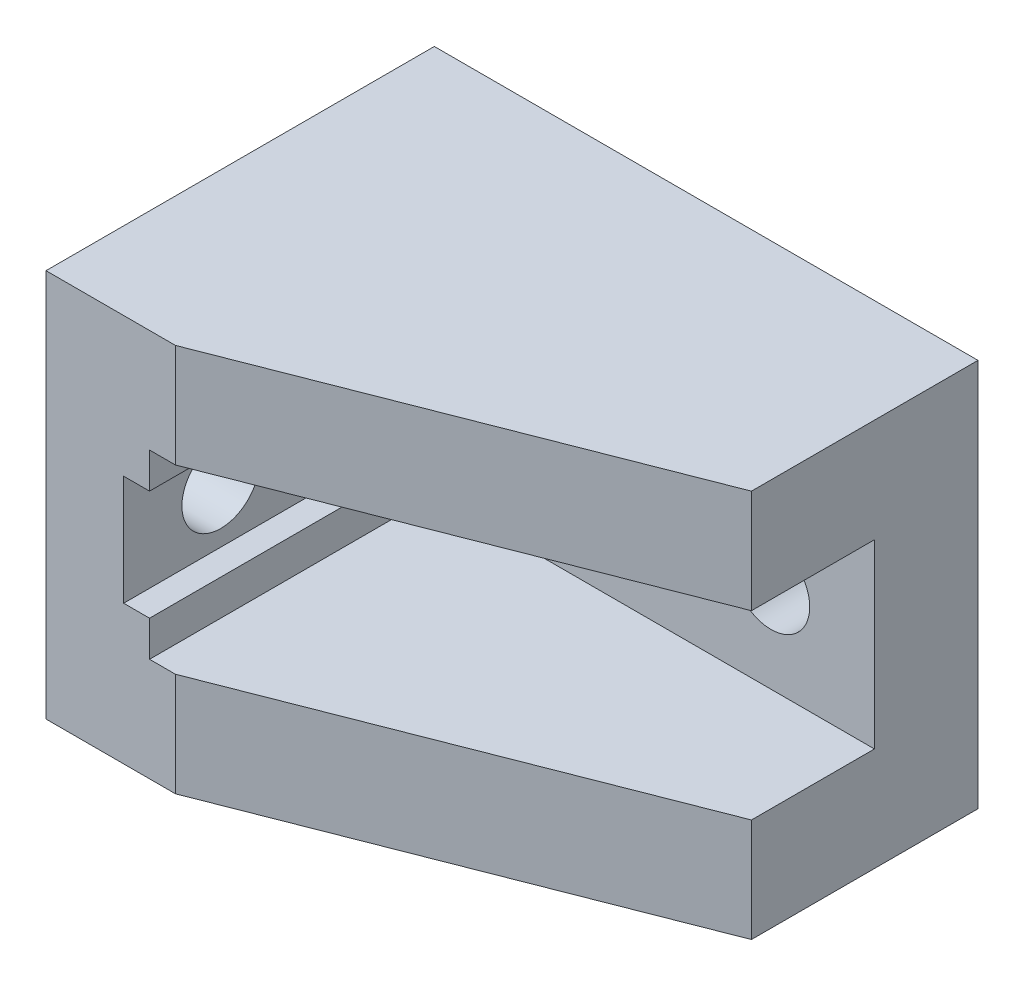
SolidWorks part; units mm, degrees
ref_plane "Front Plane" through (0, 0, 0) normal (0, 0, 1) x (1, 0, 0)
ref_plane "Top Plane" through (0, 0, 0) normal (0, 1, 0) x (1, 0, 0)
ref_plane "Right Plane" through (0, 0, 0) normal (1, 0, 0) x (0, 0, -1)
sketch "Sketch2" plane through (0, 0, 0) normal (0, 1, 0) x (1, 0, 0)
  line L0 (10, -30) -> (42, -17.5)
  line L1 (0, 0) -> (42, 0)
  line L2 (0, 0) -> (0, -30)
  line L3 (0, -30) -> (10, -30)
  line L4 (42, 0) -> (42, -17.5)
  dimension "D1" = 17.5
  dimension "D2" = 10
  dimension "D3" = 42
  dimension "D4" = 30
extrude "Boss-Extrude1" add sketch "Sketch2" along normal blind 30
shell "Shell1" thickness 8
sketch "Sketch3" plane through (8, 0, 0) normal (1, 0, 0) x (0, 0, -1)
  line L0 (-30, 15) -> (0, 15) construction
  line L1 (-30, 22) -> (-30, 8) construction
  line L3 (-15, 22) -> (-15, 8) construction
  line L7 (0, 30) -> (0, 0) construction
  line L8 (-17.5, 22) -> (-8, 22) construction
  circle A0 centre (-22.5, 15) radius 3
  circle A1 centre (-7.5, 15) radius 3
  point P8 (-15, 15)
  dimension "D2" = 6
  dimension "D1" = 15
extrude "Cut-Extrude1" cut sketch "Sketch3" against normal blind 30
sketch "Sketch4" plane through (0, 0, 8) normal (0, 0, 1) x (1, 0, 0)
  line L0 (8, 15) -> (42, 15) construction
  line L2 (42, 22) -> (42, 8) construction
  line L3 (25, 15) -> (25, 8) construction
  line L4 (42, 8) -> (8, 8) construction
  circle A0 centre (16, 15) radius 3
  circle A1 centre (34, 15) radius 3
  dimension "D1" = 18
  dimension "D2" = 6
extrude "Cut-Extrude2" cut sketch "Sketch4" against normal blind 10
sketch "Sketch6" plane through (0, 0, 0) normal (-1, 0, 0) x (0, 0, 1)
  line L4 (0, 0) -> (30, 0)
  line L5 (30, 0) -> (30, 30)
  line L6 (30, 30) -> (0, 30)
  line L7 (0, 30) -> (0, 0)
  line L8 (0, 0) -> (30, 0)
  line L9 (30, 0) -> (30, 30)
  line L10 (30, 30) -> (0, 30)
  line L11 (0, 30) -> (0, 0)
  circle A1 centre (22.5, 15) radius 3
  circle A2 centre (22.5, 15) radius 3
  circle A3 centre (7.5, 15) radius 3
  circle A4 centre (7.5, 15) radius 3
  dimension "D1" = 0
  dimension "D2" = 0
  dimension "D3" = 0
extrude "Boss-Extrude3" [suppressed] add sketch "Sketch6" along normal blind 2
sketch "Sketch8" plane through (0, 0, 8) normal (0, 0, 1) x (1, 0, 0)
  line L1 (6, 10.75) -> (9.5, 10.75)
  line L2 (6, 10.75) -> (6, 19.25)
  line L3 (6, 19.25) -> (9.5, 19.25)
  line L4 (9.5, 10.75) -> (9.5, 19.25)
  line L5 (6, 10.75) -> (9.5, 19.25) construction
  line L6 (6, 19.25) -> (9.5, 10.75) construction
  line L7 (7.75, 15) -> (8, 15) construction
  line L8 (8, 17.958) -> (8, 12.042) construction
  line L9 (8, 22) -> (8, 8) construction
  point P0 (7.75, 15)
  dimension "D1" = 8.5
  dimension "D2" = 3.5
  dimension "D3" = 2
extrude "Cut-Extrude3" cut sketch "Sketch8" against normal through all both and the other way through all
